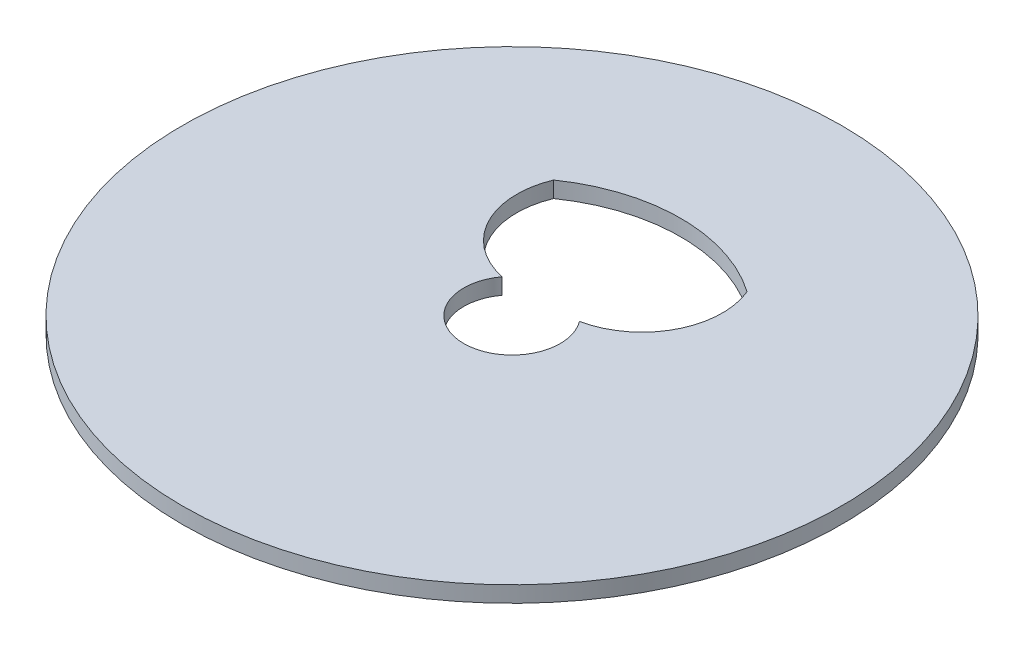
SolidWorks part; units mm, degrees
ref_plane "Front Plane" through (0, 0, 0) normal (0, 0, 1) x (1, 0, 0)
ref_plane "Top Plane" through (0, 0, 0) normal (0, 1, 0) x (1, 0, 0)
ref_plane "Right Plane" through (0, 0, 0) normal (1, 0, 0) x (0, 0, -1)
sketch "Sketch1" plane through (0, 0, 0) normal (0, 1, 0) x (1, 0, 0)
  circle A0 centre (0, 0) radius 41
  arc A1 (-13.0653, 16.4407) -> (13.0653, 16.4407) centre (0, 0) ccw
  circle A3 centre (0, 0) radius 21
  arc A4 (-4.8067, 3.5911) -> (4.8067, 3.5911) centre (0, 0) ccw
  arc A5 (-4.8067, 3.5911) -> (-12.0377, 17.2073) centre (-2.7963, 13.387) cw
  arc A6 (12.0377, 17.2073) -> (4.8067, 3.5911) centre (2.7963, 13.387) cw
  dimension "D1" = 82
  dimension "D3" = 12
  dimension "D4" = 10
  dimension "D5" = 10
extrude "Boss-Extrude1" add sketch "Sketch1" along normal blind 2 contours A0 A3 A1 | A3 A6 A4 A5 A1
